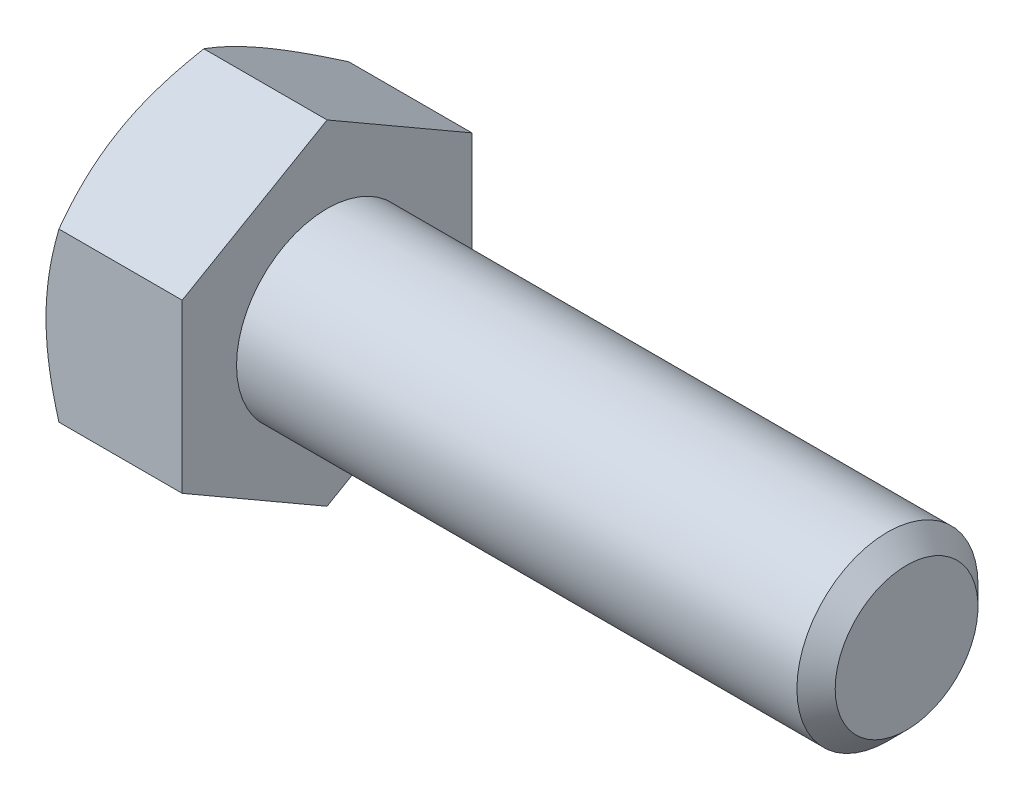
SolidWorks part; units mm, degrees
ref_plane "Plane1" through (0, 0, 0) normal (0, 0, 1) x (1, 0, 0)
ref_plane "Plane2" through (0, 0, 0) normal (0, 1, 0) x (1, 0, 0)
ref_plane "Plane3" through (0, 0, 0) normal (1, 0, 0) x (0, 0, -1)
sketch "Sketch1" plane through (0, 0, 0) normal (1, 0, 0) x (0, 0, -1)
  line L0 (6.35, 3.6662) -> (6.35, -3.6662)
  line L1 (-6.35, 3.6662) -> (-6.35, -3.6662)
  line L2 (6.35, -3.6662) -> (0, -7.3323)
  line L3 (0, -7.3323) -> (-6.35, -3.6662)
  line L4 (6.35, 3.6662) -> (0, 7.3323)
  line L5 (0, 7.3323) -> (-6.35, 3.6662)
  dimension "Width_flats" = 12.7
  dimension "D2" = 120
  dimension "D3" = 6.35
  dimension "D4" = 6.35
  dimension "D5" = 6.35
extrude "BaseHead" add sketch "Sketch1" along normal blind 5.969
sketch "BodySke" plane through (0, 0, 0) normal (0, 0, 1) x (1, 0, 0)
  line L0 (0, 3.6662) -> (0, -3.6662) construction
  line L1 (0, 0) -> (31.369, 0)
  line L2 (0, 0) -> (0, 3.9688)
  line L3 (0, 3.9688) -> (30.5295, 3.9688)
  line L4 (31.369, 0) -> (31.369, 3.1293)
  line L5 (5.969, 7.3323) -> (5.969, 3.6662) construction
  line L6 (31.369, 3.1293) -> (30.5295, 3.9688)
  line L7 (0, 0) -> (96.52, 0) construction
  line L8 (31.369, -3.1293) -> (30.5295, -3.9688) construction
  line L9 (0, -3.9688) -> (30.5295, -3.9688) construction
  line L10 (7.3787, 15.24) -> (7.3787, -2.54) construction
  line L11 (9.144, 15.24) -> (9.144, -2.54) construction
  line L12 (5.969, 3.6662) -> (5.969, -3.6662) construction
  dimension "Length" = 25.4
  dimension "Body_ch_ang" = 45
  dimension "Diameter" = 7.9375
  dimension "Minor_dia" = 6.2586
  dimension "Advance" = 1.4097
  dimension "Thread_nom" = 22.225
revolve "BaseBody" add sketch "BodySke" angle 360 about L7
cosmetic thread "ThreadCosmetic" [suppressed] parameters "Thread_length"=22.225, "Thread_minor"=6.2586
sketch "Sketch3" plane through (0, 0, 0) normal (0, 0, 1) x (1, 0, 0)
  line L0 (0, 6.35) -> (4.2333, 13.6823)
  line L1 (0, 7.3323) -> (0, 3.6662) construction
  line L2 (4.2333, 13.6823) -> (4.2333, 20.0323)
  line L3 (4.2333, 20.0323) -> (-12.7, 20.0323)
  line L4 (-12.7, 20.0323) -> (-12.7, 6.35)
  line L5 (-12.7, 6.35) -> (0, 6.35)
  line L6 (0, 0) -> (99.06, 0) construction
  line L7 (5.969, 7.3323) -> (0, 7.3323) construction
  dimension "D1" = 6.35
  dimension "D2" = 6.35
  dimension "D3" = 12.7
  dimension "D4" = 6.35
  dimension "Head_ch_ang" = 30
revolve "HeadChamfer" cut sketch "Sketch3" angle 360 about L6
fillet "HeadFillet" [suppressed] radius 0.762
sketch "ThdSchSke" plane through (0, 0, 0) normal (0, 0, 1) x (1, 0, 0)
  line L0 (9.144, -3.1293) -> (8.5562, -3.9688)
  line L1 (9.144, -3.1293) -> (9.7318, -3.9688)
  line L2 (9.7318, -3.9688) -> (9.7318, -4.9609)
  line L3 (-3.175, 0) -> (5.1513, 0) construction
  line L5 (9.7318, -4.9609) -> (8.5562, -4.9609)
  line L6 (8.5562, -4.9609) -> (8.5562, -3.9688)
  dimension "Thread_minor" = 6.2586
  dimension "Diameter" = 7.9375
  dimension "Start" = 9.144
  dimension "SideAngle" = 55
  dimension "VeeAngle" = 70
  dimension "Overcut" = 9.9219
revolve "ThreadSchematic" [suppressed] cut sketch "ThdSchSke" angle 360 about L3
pattern_linear "ThdSchPat" [suppressed]
equation "\"D3@Sketch1\" = \"Width_flats@Sketch1\" / 2"
equation "\"D4@Sketch1\" = \"D3@Sketch1\""
equation "\"D5@Sketch1\" = \"D4@Sketch1\""
equation "\"Thread_minor@ThreadCosmetic\" = \"Minor_dia@BodySke\""
equation "\"D1@Sketch3\" = \"Width_flats@Sketch1\" / 2"
equation "\"Thread_length@ThreadCosmetic\" = ((sgn( (\"Length@BodySke\" - \"Advance@BodySke\" ) - \"Thread_nom@BodySke\" )-1)*( (\"Length@BodySke\" - \"Advance@BodySke\" ) - \"Thread_nom@BodySke\" ))/-2+ \"Thread_nom@BodySke\""
equation "\"Thread_minor@ThdSchSke\" = \"Minor_dia@BodySke\""
equation "\"Diameter@ThdSchSke\" = \"Diameter@BodySke\""
equation "\"Overcut@ThdSchSke\" = \"Diameter@BodySke\" * 1.25"
equation "\"Start@ThdSchSke\" = \"Head_ht@BaseHead\" + \"Length@BodySke\" - \"Thread_length@ThreadCosmetic\"  '---Non-countersunk---"
equation "\"Num_threads@ThdSchPat\" = int( \"Thread_length@ThreadCosmetic\" / \"Advance@BodySke\" + 0.999 )  + 1"
equation "\"Advance@ThdSchPat\" = \"Thread_length@ThreadCosmetic\" /  (\"Num_threads@ThdSchPat\" - 1) 'relax it"
equation "\"Num_threads@ThdSchPat\" = \"Num_threads@ThdSchPat\" - sgn( \"Num_threads@ThdSchPat\" - 1) '---chamfered tips only---"
